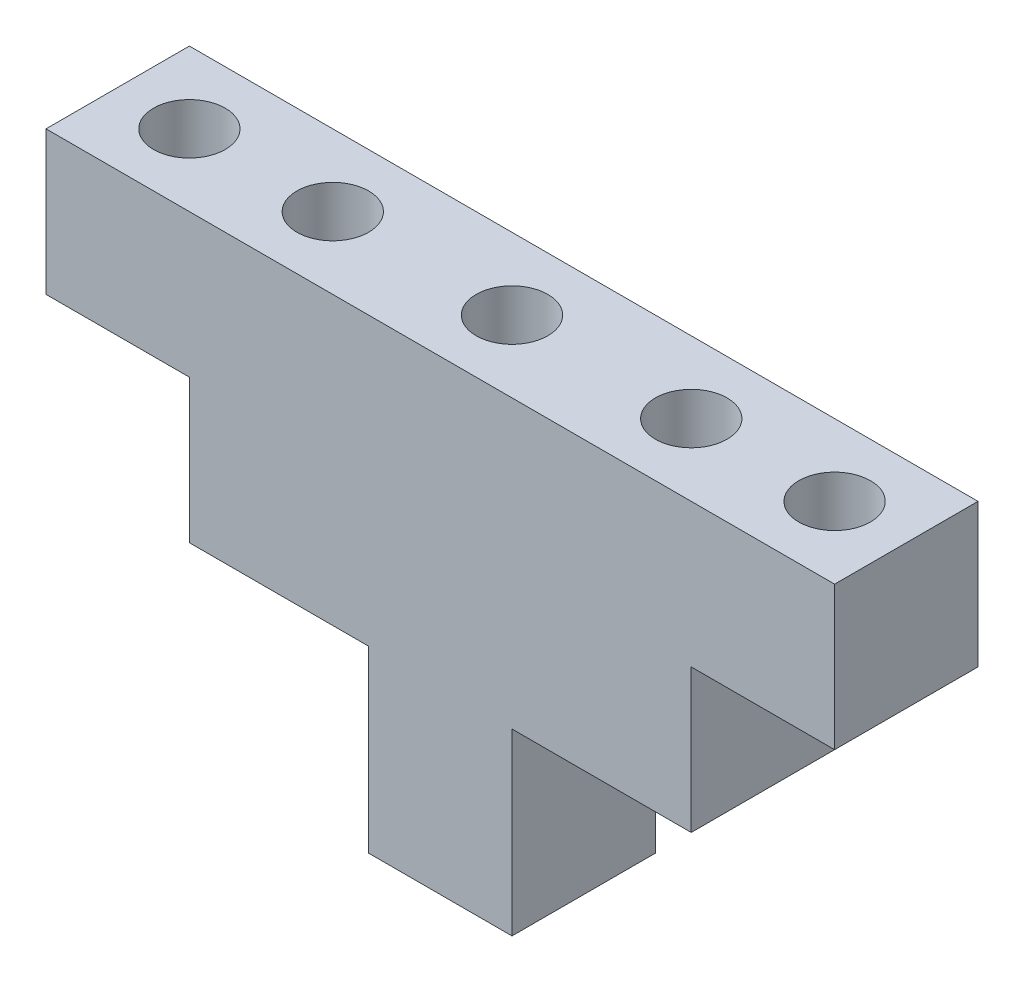
SolidWorks part; units mm, degrees
ref_plane "Front Plane" through (0, 0, 0) normal (0, 0, 1) x (1, 0, 0)
ref_plane "Top Plane" through (0, 0, 0) normal (0, 1, 0) x (1, 0, 0)
ref_plane "Right Plane" through (0, 0, 0) normal (1, 0, 0) x (0, 0, -1)
sketch "Sketch1" plane through (0, 0, 0) normal (0, 0, 1) x (1, 0, 0)
  line L0 (-22.225, 12.7) -> (-34.925, 12.7) construction
  line L1 (-22.225, -12.7) -> (22.225, -12.7)
  line L2 (-22.225, -12.7) -> (-22.225, 12.7)
  line L3 (-22.225, 12.7) -> (22.225, 12.7)
  line L4 (22.225, -12.7) -> (22.225, 12.7)
  line L5 (-22.225, -12.7) -> (22.225, 12.7) construction
  line L6 (-22.225, 12.7) -> (22.225, -12.7) construction
  line L8 (-34.925, 12.7) -> (34.925, 12.7)
  line L9 (-34.925, 12.7) -> (-34.925, 0)
  line L10 (-34.925, 0) -> (34.925, 0)
  line L11 (34.925, 12.7) -> (34.925, 0)
  point P0 (0, 0)
extrude "Boss-Extrude1" add sketch "Sketch1" along normal blind 12.7 contours L10 L2 L1 L4 | L2 L10 L4 L3 | L9 L10 L2 L8 | L11 L8 L4 L10
sketch "Sketch2" plane through (0, -12.7, 0) normal (0, -1, 0) x (1, 0, 0)
  line L0 (22.225, 12.7) -> (22.225, 0) construction
  circle A0 centre (-15.875, 6.35) radius 3.175
  circle A1 centre (15.875, 6.35) radius 3.175
  dimension "D1" = 31.75
  dimension "D2" = 6.35
extrude "Cut-Extrude1" cut sketch "Sketch2" against normal blind 25.4
sketch "Sketch3" plane through (0, 0, 0) normal (0, -1, 0) x (1, 0, 0)
  circle A0 centre (-28.575, 6.35) radius 3.175
  circle A1 centre (28.575, 6.35) radius 3.175
extrude "Cut-Extrude2" cut sketch "Sketch3" against normal blind 25.4
sketch "Sketch4" plane through (0, -12.7, 0) normal (0, -1, 0) x (1, 0, 0)
  line L0 (-22.225, 12.7) -> (-6.35, 12.7) construction
  line L1 (-22.225, 12.7) -> (22.225, 12.7) construction
  line L2 (22.225, 12.7) -> (6.35, 12.7) construction
  line L3 (-6.35, 12.7) -> (-6.35, 0)
  line L4 (-22.225, 0) -> (22.225, 0) construction
  line L5 (-6.35, 0) -> (6.35, 0)
  line L6 (6.35, 0) -> (6.35, 12.7)
  line L7 (6.35, 12.7) -> (-6.35, 12.7)
extrude "Boss-Extrude2" add sketch "Sketch4" along normal blind 15.875
sketch "Sketch5" plane through (0, -28.575, 0) normal (0, -1, 0) x (1, 0, 0)
  line L1 (-22.225, 12.7) -> (22.225, 12.7)
  line L2 (-22.225, 12.7) -> (-22.225, 0)
  line L3 (-22.225, 0) -> (22.225, 0)
  line L4 (22.225, 12.7) -> (22.225, 0)
  circle A0 centre (-15.875, 6.35) radius 3.175
  circle A1 centre (15.875, 6.35) radius 3.175
extrude "Boss-Extrude3" add sketch "Sketch5" along normal blind 12.7
sketch "Sketch6" plane through (0, -41.275, 0) normal (0, -1, 0) x (1, 0, 0)
  line L1 (-22.225, 12.7) -> (22.225, 12.7)
  line L2 (-22.225, 12.7) -> (-22.225, 0)
  line L3 (-22.225, 0) -> (22.225, 0)
  line L4 (22.225, 12.7) -> (22.225, 0)
extrude "Cut-Extrude3" cut sketch "Sketch6" against normal blind 12.7
sketch "Sketch7" plane through (0, -28.575, 0) normal (0, -1, 0) x (1, 0, 0)
  circle A0 centre (0, 6.35) radius 3.175
extrude "Cut-Extrude4" cut sketch "Sketch7" against normal up to next
